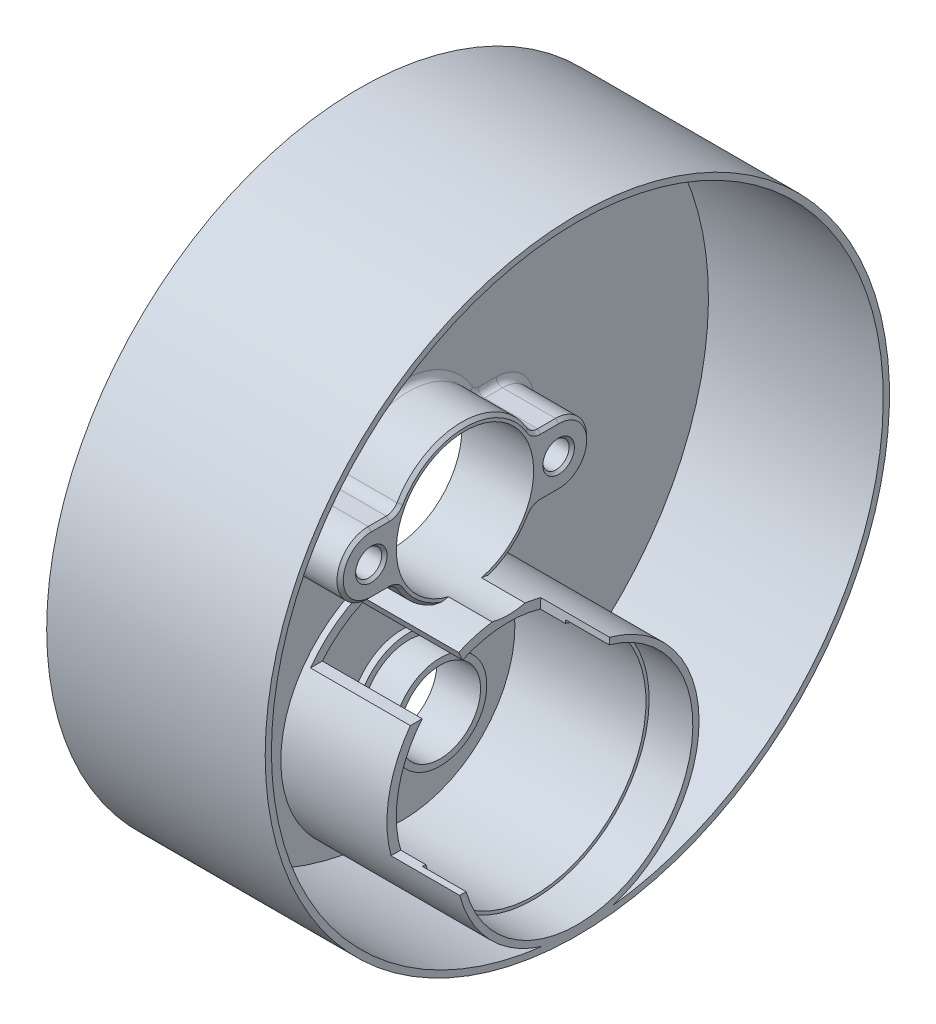
SolidWorks part; units mm, degrees
material "1060 Сплав"
ref_plane "Спереди" through (0, 0, 0) normal (0, 0, 1) x (1, 0, 0)
ref_plane "Сверху" through (0, 0, 0) normal (0, 1, 0) x (1, 0, 0)
ref_plane "Справа" through (0, 0, 0) normal (1, 0, 0) x (0, 0, -1)
sketch "Эскиз1" plane through (0, 0, 0) normal (0, 0, 1) x (1, 0, 0)
  line L0 (0, 0) -> (26039.5549, 0) construction
  line L1 (-27, 7.5) -> (-27, 8.5)
  line L2 (0, 19.5) -> (-29, 19.5)
  line L3 (-29, 19.5) -> (-29, 6.5)
  line L4 (-29, 6.5) -> (-22, 6.5)
  line L5 (-22, 6.5) -> (-22, 7.5)
  line L6 (-22, 7.5) -> (-27, 7.5)
  line L7 (-28, 8.5) -> (-28, 18)
  line L8 (-28, 18) -> (-7, 18)
  line L9 (-7, 18) -> (-7, 18.5)
  line L10 (-7, 18.5) -> (0, 18.5)
  line L11 (0, 18.5) -> (0, 19.5)
  line L12 (-27, 8.5) -> (-28, 8.5)
  dimension "D1" = 18.5
  dimension "D2" = 1
  dimension "D3" = 18
  dimension "D4" = 7
  dimension "D5" = 21
  dimension "D6" = 1
  dimension "D7" = 1
  dimension "D8" = 1
  dimension "D9" = 7.5
  dimension "D10" = 1
  dimension "D11" = 13
  dimension "D12" = 0.5
  dimension "D13" = 5
revolve "Повернуть1" add sketch "Эскиз1" angle 360 about L0
sketch "Эскиз2" plane through (0, 0, 0) normal (1, 0, 0) x (0, 0, -1)
  line L0 (0, 0) -> (0, 50000) construction
  line L1 (5.1563, 18.8059) -> (5, 16.2481)
  line L2 (5, 0) -> (5, 50000) construction
  line L3 (0, 0) -> (0, -5) construction
  line L4 (0, -5) -> (-50000, -5) construction
  line L5 (-18.8481, -5) -> (-16.2481, -5)
  line L6 (-5, 0) -> (-5, 50000) construction
  arc A0 (5, 16.2481) -> (-16.2481, -5) centre (0, 0) ccw
  arc A1 (-18.8481, -5) -> (5.1563, 18.8059) centre (0, 0) cw
  circle A2 centre (0, 0) radius 19.5 construction
  dimension "D3" = 17
  dimension "D4" = 19.5
  dimension "D1" = 5
  dimension "D2" = 5
  dimension "D5" = 2.5626
  dimension "D6" = 0
extrude "Вырез-Вытянуть1" cut sketch "Эскиз2" against normal blind 11 contours A0 L5 A1 L1
sketch "Эскиз3" plane through (0, 0, 0) normal (1, 0, 0) x (0, 0, -1)
  line L3 (-40, 11.5) -> (-12.52, 11.5)
  line L4 (0, 0) -> (-20535.6471, 45588.2353) construction
  line L5 (-6.9821, 15.5) -> (-13.2408, 29.394)
  line L6 (-13.2408, 29.394) -> (-40, 11.5)
  line L7 (0, 15.5) -> (-50000, 15.5) construction
  circle A0 centre (0, 0) radius 15.5 construction
  circle A1 centre (0, 0) radius 11.5 construction
  arc A2 (-6.9821, 15.5) -> (-12.52, 11.5) centre (0, 0) ccw
  dimension "D1" = 31
  dimension "D2" = 23
  dimension "D4" = 34
  dimension "D3" = 15.2386
  dimension "D5" = 32.1908
extrude "Вырез-Вытянуть2" cut sketch "Эскиз3" against normal blind 27
sketch "Эскиз4" plane through (-29, 0, 0) normal (-1, 0, 0) x (0, 0, 1)
  circle A1 centre (0, 30) radius 50
  circle A3 centre (0, 0) radius 6.5 construction
  circle A4 centre (0, 0) radius 6.5
  dimension "D2" = 100
  dimension "D5" = 13
  dimension "D1" = 30
  dimension "D4" = 30
extrude "Бобышка-Вытянуть1" add sketch "Эскиз4" against normal blind 1
sketch "Эскиз5" plane through (-29, 0, 0) normal (-1, 0, 0) x (0, 0, 1)
  circle A0 centre (0, 30) radius 50
  circle A1 centre (0, 30) radius 49
  dimension "D1" = 100
  dimension "D2" = 98
extrude "Бобышка-Вытянуть2" add sketch "Эскиз5" against normal blind 29 and the other way blind 6
sketch "Эскиз15" plane through (-28, 0, 0) normal (-1, 0, 0) x (0, 0, 1)
  circle A0 centre (0, 30) radius 11
  circle A1 centre (0, 30) radius 12
  dimension "D1" = 1
  dimension "D2" = 24
extrude "Бобышка-Вытянуть3" add sketch "Эскиз15" against normal blind 10 and the other way blind 1.5
sketch "Эскиз17" plane through (-28, 0, 0) normal (1, 0, 0) x (0, 0, -1)
  line L0 (0, 30) -> (-15, 30) construction
  line L1 (-15, 35) -> (-10.9087, 35)
  line L2 (-15, 25) -> (-10.9087, 25)
  arc A0 (-15, 35) -> (-15, 25) centre (-15, 30) ccw
  arc A1 (4.6498, 18.9375) -> (-4.6498, 18.9375) centre (0, 30) ccw construction
  arc A2 (-10.9087, 35) -> (-10.9087, 25) centre (0, 30) ccw
  dimension "D1" = 15
  dimension "D2" = 10
extrude "Бобышка-Вытянуть4" add sketch "Эскиз17" along normal blind 10
hole_wizard "Отверстие обработанное метчиком M5x0.81" positions "Эскиз18" profile "Эскиз19" tap size "M5x0.8" standard "Ansi Metric" end condition through all
sketch "Эскиз18" plane through (-18, 0, 0) normal (1, 0, 0) x (0, 0, -1)
  point P0 (-15, 30)
sketch "Эскиз19" plane through (-18, 30, 15) normal (0, 1, 0) x (0, 0, -1)
  line L0 (0, 0) -> (0, 17)
  line L1 (0, 17) -> (2.1, 17)
  line L2 (2.1, 17) -> (2.1, 0.425)
  line L3 (2.1, 0.425) -> (2.525, 0)
  line L5 (2.525, 0) -> (0, 0)
  line L6 (-2.1, 0.425) -> (-2.525, 0) construction
  line L11 (0, -6.35) -> (0, 107.95) construction
  dimension "Диаметр проходного сверла" = 4.2
  dimension "Глубина проходного сверла" = 17
  dimension "Диаметр передней зенковки" = 5.05
  dimension "Угол передней зенковки" = 90
cosmetic thread "Отверстие резьбы1" parameters "D2"=5
fillet "Скругление1" radius 2 2 edges at (-23, 25, 10.9087) (-23, 35, 10.9087)
mirror "Зеркальное отражение1" about plane through (0, 0, 0) normal (0, 0, 1) of "Скругление1", "Отверстие обработанное метчиком M5x0.81", "Бобышка-Вытянуть4"
fillet "Скругление2" radius 1 13 edges at (-28, 20.9985, -7.9356) (-28, 24.7321, -11.1244) (-28, 25, -13.5622) (-28, 30, -20) (-28, 35, -13.5622) (-28, 35.2679, -11.1244) (-28, 20.9985, 7.9356) (-28, 24.7321, 11.1244) (-28, 25, 13.5622) (-28, 30, 20) (-28, 35, 13.5622) (-28, 35.2679, 11.1244) (-28, 42, 0)
chamfer "Фаска1" distance 0.5 angle 45 13 edges at (-18, 20.9985, 7.9356) (-18, 20.9985, -7.9356) (-18, 24.7321, 11.1244) (-18, 24.7321, -11.1244) (-18, 25, 13.5622) (-18, 25, -13.5622) (-18, 30, 20) (-18, 30, -20) (-18, 35, 13.5622) (-18, 35, -13.5622) (-18, 35.2679, 11.1244) (-18, 35.2679, -11.1244) (-18, 42, 0)
sketch "Эскиз16" plane through (-28, 0, 0) normal (1, 0, 0) x (0, 0, -1)
  circle A0 centre (0, 30) radius 11
  arc A1 (2.6373, 19.3208) -> (-2.6373, 19.3208) centre (0, 30) ccw construction
extrude "Вырез-Вытянуть4" cut sketch "Эскиз16" against normal through all both and the other way through all
sketch "Эскиз12" plane through (-29, 0, 0) normal (-1, 0, 0) x (0, 0, 1)
  line L0 (0, 30) -> (0, 56.4) construction
  circle A0 centre (0, 56.4) radius 5
  dimension "D2" = 10
  dimension "D1" = 26.4
extrude "Вырез-Вытянуть3" cut sketch "Эскиз12" against normal up to next
hole_wizard "Сверление под метчик M2x0.41" positions "Эскиз13" profile "Эскиз14" hole size "M2x0.4" standard "Ansi Metric" end condition through all
sketch "Эскиз13" plane through (-29, 0, 0) normal (-1, 0, 0) x (0, 0, 1)
  line L0 (0, 56.4) -> (0, 62.9) construction
  point P0 (0, 62.9)
  dimension "D1" = 6.5
sketch "Эскиз14" plane through (-29, 62.9, 0) normal (0, 1, 0) x (0, 0, 1)
  line L0 (0, 0) -> (0, 29)
  line L1 (0, 29) -> (0.8, 29)
  line L2 (0.8, 29) -> (0.8, 0)
  line L5 (0.8, 0) -> (0, 0)
  line L11 (0, -6.35) -> (0, 107.95) construction
  dimension "Диаметр сквозного отверстия" = 1.6
  dimension "Глубина сквозного отверстия" = 29
pattern_circular "Круговой массив1" count 3 over 360 about axis through (0, 56.4, 0) along (1, 0, 0) of "Сверление под метчик M2x0.41"
